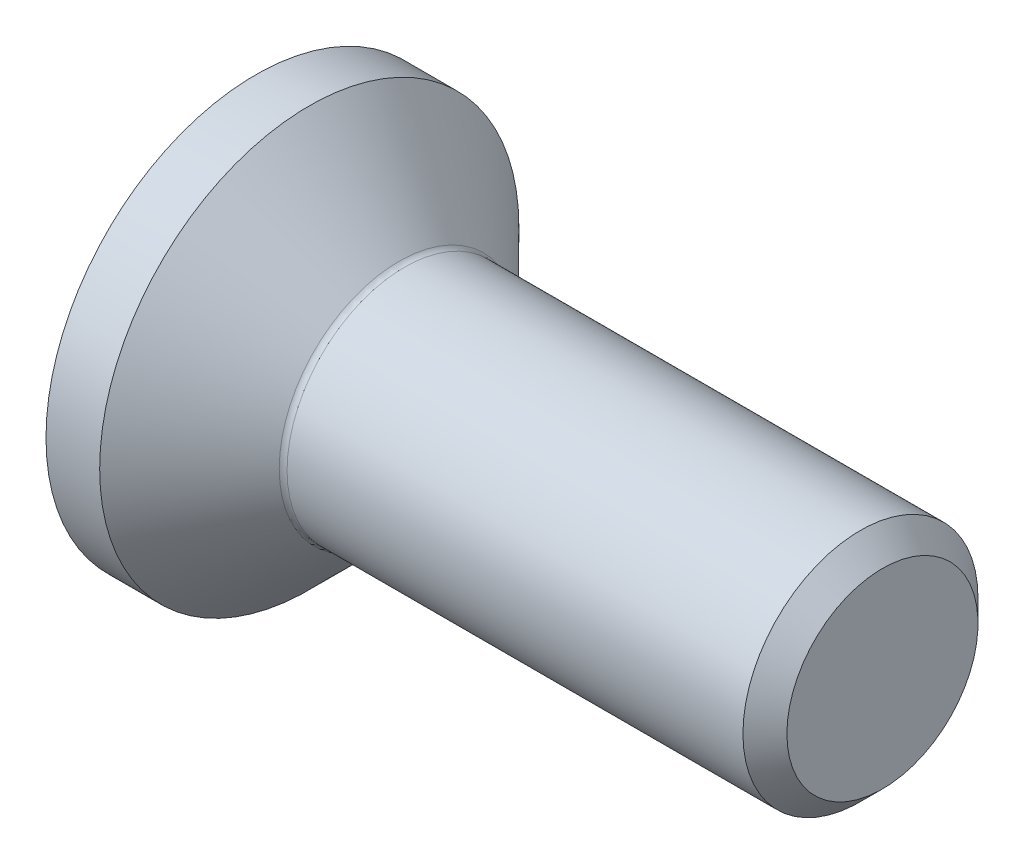
SolidWorks part; units mm, degrees
ref_plane "Plane1" through (0, 0, 0) normal (0, 0, 1) x (1, 0, 0)
ref_plane "Plane2" through (0, 0, 0) normal (0, 1, 0) x (1, 0, 0)
ref_plane "Plane3" through (0, 0, 0) normal (1, 0, 0) x (0, 0, -1)
sketch "BodySke" plane through (0, 0, 0) normal (0, 0, 1) x (1, 0, 0)
  line L0 (0, 0) -> (0, 2.675)
  line L1 (0.685, 2.675) -> (1.86, 1.5)
  line L2 (0, 2.675) -> (0.685, 2.675)
  line L3 (1.86, 1.5) -> (7.7195, 1.5)
  line L4 (8, 1.2195) -> (8, 0)
  line L5 (8, 0) -> (0, 0)
  line L6 (0, 0) -> (127, 0) construction
  line L7 (0.685, -2.675) -> (1.86, -1.5) construction
  line L8 (8, 1.2195) -> (7.7195, 1.5)
  line L9 (0, -2.675) -> (0.685, -2.675) construction
  line L10 (8, -1.2195) -> (7.7195, -1.5) construction
  line L11 (2.36, 7.85) -> (2.36, -14.375) construction
  line L12 (0, 19.05) -> (0, -3.175) construction
  dimension "D1" = 0.685
  dimension "Diameter" = 3
  dimension "Head_ht" = 1.86
  dimension "Length" = 8
  dimension "Body_ch_ang" = 45
  dimension "Head_dia" = 5.35
  dimension "Minor_dia" = 2.439
  dimension "Head_ang" = 90
  dimension "Advance" = 0.5
  dimension "Thread_nom" = 8
revolve "BaseBody" add sketch "BodySke" angle 360 about L6
cosmetic thread "ThreadCosmetic" [suppressed] parameters "Thread_length"=5.14, "Thread_minor"=2.439
fillet "Fillet1" radius 0.1 1 edges at (1.86, 0, 1.5)
sketch "Sketch2" plane through (0, 0, 0) normal (0, 0, 1) x (1, 0, 0)
  line L0 (0, 1) -> (1.1, 1)
  line L1 (1.1, 1) -> (1.6774, 0)
  line L2 (0, 0) -> (127, 0) construction
  line L3 (1.6774, 0) -> (0, 0)
  line L4 (0, 0) -> (0, 1)
  line L5 (0, -1) -> (1.1, -1) construction
  line L6 (0, 0) -> (47.625, 0) construction
  line L8 (0, 2.675) -> (0, -2.675) construction
  dimension "D2" = 60
  dimension "PreBroach_depth" = 1.1
  dimension "PreBroach_dia" = 2
revolve "PreBroach" cut sketch "Sketch2" angle 360 about L6
sketch "Sketch3" plane through (0, 0, 0) normal (-1, 0, 0) x (0, 0, 1)
  line L0 (-1, -0.5774) -> (-1, 0.5774)
  line L1 (-1, 0.5774) -> (0, 1.1547)
  line L2 (0, 1.1547) -> (1, 0.5774)
  line L3 (1, 0.5774) -> (1, -0.5774)
  line L4 (1, -0.5774) -> (0, -1.1547)
  line L5 (0, -1.1547) -> (-1, -0.5774)
  dimension "D1" = 1
  dimension "D2" = 1
  dimension "D3" = 2
  dimension "Hex_size" = 2
extrude "Hex" cut sketch "Sketch3" against normal blind 1.1
sketch "ThdSchSke" plane through (0, 0, 0) normal (0, 0, 1) x (1, 0, 0)
  line L0 (2.86, -1.2195) -> (2.6636, -1.5)
  line L1 (2.86, -1.2195) -> (3.0564, -1.5)
  line L2 (3.0564, -1.5) -> (3.0564, -1.875)
  line L3 (-3.175, 0) -> (5.1513, 0) construction
  line L4 (0, 2.675) -> (0, -2.675) construction
  line L5 (3.0564, -1.875) -> (2.6636, -1.875)
  line L6 (2.6636, -1.875) -> (2.6636, -1.5)
  dimension "Thread_minor" = 2.439
  dimension "Diameter" = 3
  dimension "Start" = 2.86
  dimension "SideAngle" = 55
  dimension "VeeAngle" = 70
  dimension "Overcut" = 3.75
revolve "ThreadSchematic" [suppressed] cut sketch "ThdSchSke" angle 360 about L3
pattern_linear "ThdSchPat" [suppressed]
equation "\"Thread_minor@ThreadCosmetic\"  =  \"Minor_dia@BodySke\""
equation "\"D1@Sketch3\" = \"Hex_size@Sketch3\" / 2"
equation "\"D2@Sketch3\" = \"D1@Sketch3\""
equation "\"D3@Sketch3\" = \"Hex_size@Sketch3\""
equation "\"Thread_length@ThreadCosmetic\" = ((sgn( (\"Length@BodySke\" - \"Advance@BodySke\" * 2.0 - \"Head_ht@BodySke\" ) - \"Thread_nom@BodySke\" )-1)*( (\"Length@BodySke\" - \"Advance@BodySke\" * 2.0 - \"Head_ht@BodySke\" ) - \"Thread_nom@BodySke\" ))/-2+ \"Thread_nom@BodySke\""
equation "\"Thread_minor@ThdSchSke\" = \"Minor_dia@BodySke\""
equation "\"Diameter@ThdSchSke\" = \"Diameter@BodySke\""
equation "\"Overcut@ThdSchSke\" = \"Diameter@BodySke\" * 1.25"
equation "\"Start@ThdSchSke\" = 0.000001 + \"Length@BodySke\" - \"Thread_length@ThreadCosmetic\"  '---Countersunk---"
equation "\"Num_threads@ThdSchPat\" = int( \"Thread_length@ThreadCosmetic\" / \"Advance@BodySke\" + 0.999 )  + 1"
equation "\"Advance@ThdSchPat\" = \"Thread_length@ThreadCosmetic\" /  (\"Num_threads@ThdSchPat\" - 1) 'relax it"
equation "\"Num_threads@ThdSchPat\" = \"Num_threads@ThdSchPat\" - sgn( \"Num_threads@ThdSchPat\" - 1) '---chamfered tips only---"
